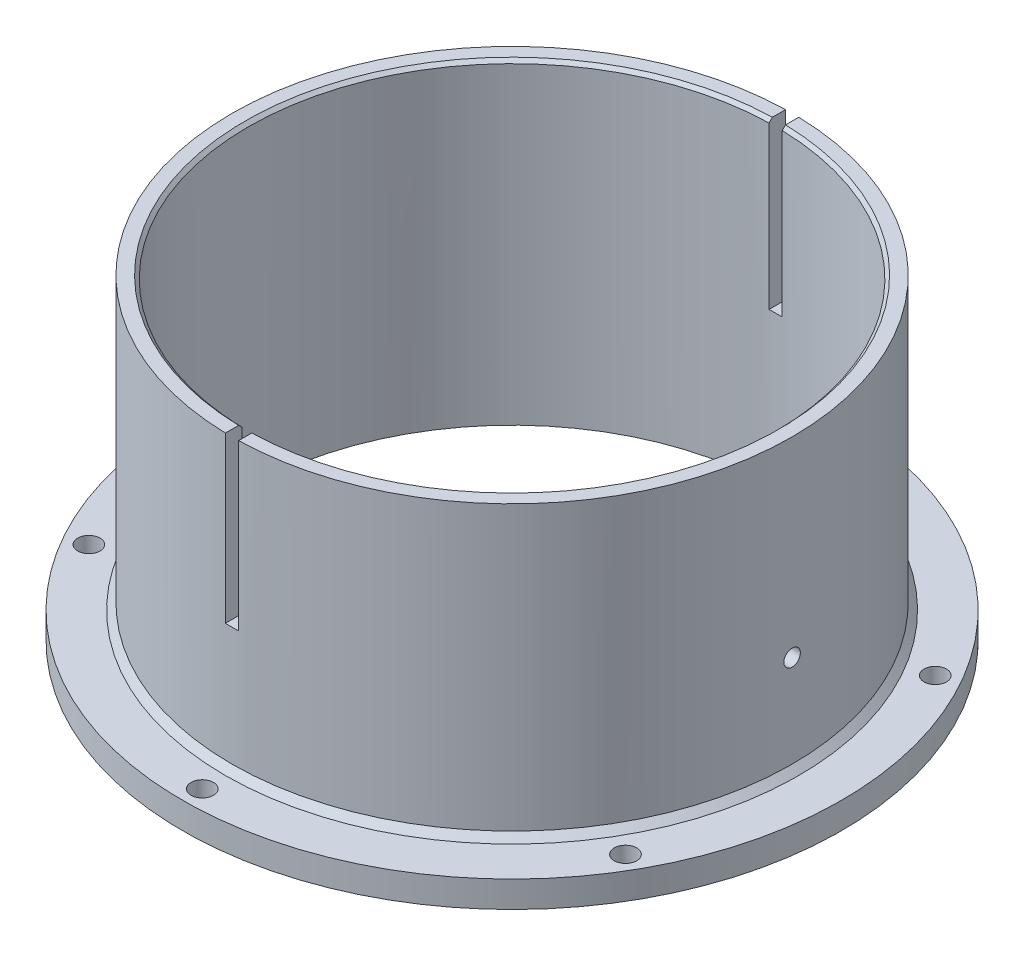
SolidWorks part; units mm, degrees
material "1060 合金"
ref_plane "前视基准面" through (0, 0, 0) normal (0, 0, 1) x (1, 0, 0)
ref_plane "上视基准面" through (0, 0, 0) normal (0, 1, 0) x (1, 0, 0)
ref_plane "右视基准面" through (0, 0, 0) normal (1, 0, 0) x (0, 0, -1)
sketch "草图1" plane through (0, 0, 0) normal (0, 0, 1) x (1, 0, 0)
  line L0 (0, 0) -> (0, 262.9765) construction
  line L1 (40, 0) -> (50, 0)
  line L2 (50, 0) -> (50, 4)
  line L3 (50, 4) -> (42.5, 4)
  line L4 (42.5, 4) -> (42.5, 48)
  line L5 (42.5, 48) -> (40, 48)
  line L6 (40, 48) -> (40, 0)
  dimension "D1" = 40
  dimension "D2" = 2.5
  dimension "D3" = 4
  dimension "D4" = 10
  dimension "D5" = 48
revolve "旋转1" add sketch "草图1" angle 360 about L0
chamfer "倒角1" distance 1 angle 45 1 edges at (0, 4, -42.5)
chamfer "倒角2" distance 0.5 angle 45 1 edges at (0, 48, -40)
sketch "草图2" plane through (0, 0, 0) normal (0, 0, 1) x (1, 0, 0)
  line L0 (0, 0) -> (0, 57.0555) construction
  line L1 (40, 48) -> (-40, 48) construction
  line L2 (-1, 23) -> (1, 23)
  line L3 (-1, 23) -> (-1, 48)
  line L4 (-1, 48) -> (1, 48)
  line L5 (1, 23) -> (1, 48)
  line L6 (-1, 23) -> (1, 48) construction
  line L7 (-1, 48) -> (1, 23) construction
  point P3 (0, 35.5)
  dimension "D1" = 2
  dimension "D2" = 25
extrude "弹性缝" cut sketch "草图2" against normal mid plane 100
hole_wizard "M3 间隙孔1" positions "草图4" profile "草图3" hole size "M3" standard "GB" end condition through all
sketch "草图4" plane through (0, 0, 0) normal (0, -1, 0) x (-1, 0, 0)
  circle A0 centre (0, 0) radius 47 construction
  point P6 (0, 47)
  point P17 (40.7032, 23.5)
  point P18 (40.7032, -23.5)
  point P19 (0, -47)
  point P20 (-40.7032, -23.5)
  point P21 (-40.7032, 23.5)
  dimension "D1" = 94
  dimension "D2" = 6
sketch "草图3" plane through (0, 0, -47) normal (1, 0, 0) x (0, 0, -1)
  line L0 (0, 0) -> (0, 48)
  line L1 (0, 48) -> (1.7, 48)
  line L2 (1.7, 48) -> (1.7, 0)
  line L5 (1.7, 0) -> (0, 0)
  line L11 (0, -6.35) -> (0, 107.95) construction
  dimension "通孔孔直径" = 3.4
  dimension "通孔孔深度" = 48
hole_wizard "M3 螺纹孔1" positions "3D草图1" profile "草图8" tap size "M3" standard "GB"
sketch3d "3D草图1"
  line L0 (0, 0, 0) -> (0, 19, 0) construction
  line L1 (0, 19, 0) -> (42.5, 19, 0) construction
  point P23 (42.5, 19, 0)
  dimension "D1" = 15
sketch "草图8" plane through (42.5, 19, 0) normal (0, 1, 0) x (0, 0, -1)
  line L0 (0, 0) -> (0, 2.5)
  line L1 (0, 2.5) -> (1.25, 2.5)
  line L2 (1.25, 2.5) -> (1.25, 0)
  line L5 (1.25, 0) -> (0, 0)
  line L11 (0, -6.35) -> (0, 107.95) construction
  dimension "螺纹线主直径" = 2.5
  dimension "通孔螺纹孔钻头深度" = 2.5
